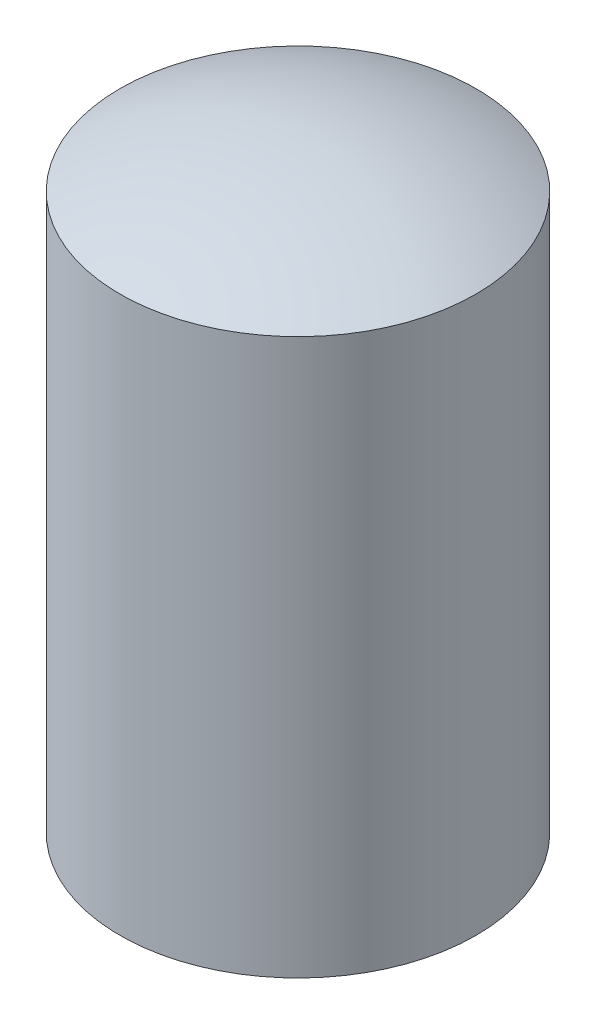
SolidWorks part; units mm, degrees
material "Plain Carbon Steel"
ref_plane "Front Plane" through (0, 0, 0) normal (0, 0, 1) x (1, 0, 0)
ref_plane "Top Plane" through (0, 0, 0) normal (0, 1, 0) x (1, 0, 0)
ref_plane "Right Plane" through (0, 0, 0) normal (1, 0, 0) x (0, 0, -1)
other "Configuration Table"
sketch "Sketch1" plane through (0, 0, 0) normal (0, 0, 1) x (1, 0, 0)
  line L0 (0, 5) -> (0, -23) construction
  line L1 (5, -1.2) -> (-5, -1.2) construction
  line L2 (5, -1.2) -> (5, -16.8)
  line L3 (5, -16.8) -> (-5, -16.8) construction
  line L4 (5, -18) -> (-5, -18) construction
  line L5 (0, -18) -> (0, 0)
  arc A0 (0, 0) -> (5, -1.2) centre (0, -11.0167) cw
  arc A1 (-5, -1.2) -> (0, 0) centre (0, -11.0167) cw construction
  arc A2 (5, -16.8) -> (0, -18) centre (0, -6.9833) cw
  arc A3 (0, -18) -> (-5, -16.8) centre (0, -6.9833) cw construction
  dimension "D1" = 1.2
  dimension "D2" = 10
  dimension "D3" = 1.2
  dimension "D4" = 5
  dimension "D5" = 5
  dimension "Length" = 18
revolve "Revolve1" add sketch "Sketch1" angle 360 about L0
